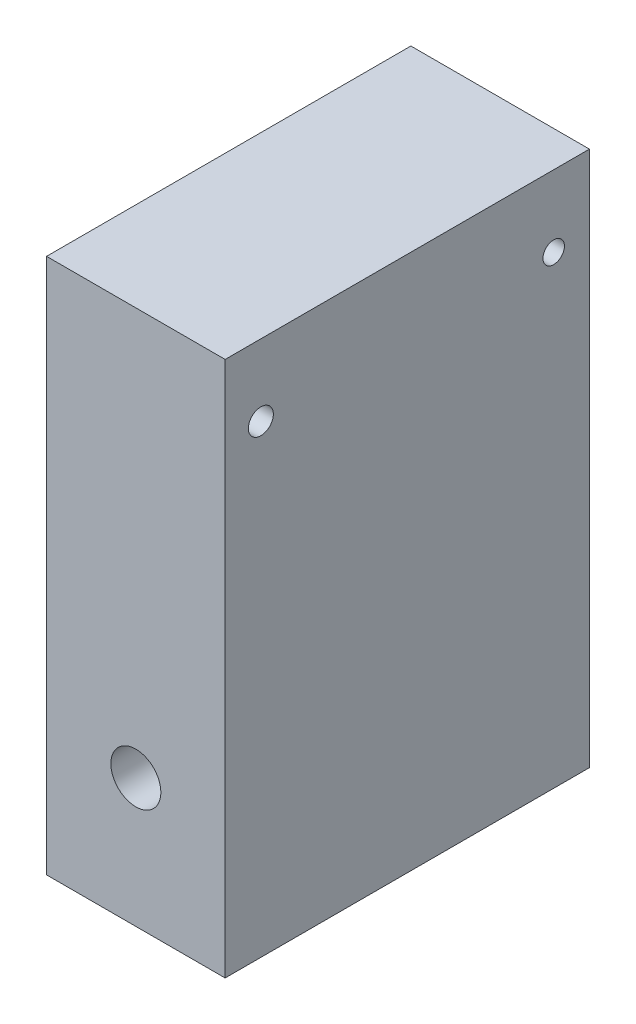
SolidWorks part; units mm, degrees
ref_plane "Plan de face" through (0, 0, 0) normal (0, 0, 1) x (1, 0, 0)
ref_plane "Plan de dessus" through (0, 0, 0) normal (0, 1, 0) x (1, 0, 0)
ref_plane "Plan de droite" through (0, 0, 0) normal (1, 0, 0) x (0, 0, -1)
sketch "Esquisse1" plane through (0, 0, 0) normal (0, 0, 1) x (1, 0, 0)
  line L1 (-6.525, 5.3902) -> (18.475, 5.3902)
  line L2 (-6.525, 5.3902) -> (-6.525, -69.6098)
  line L3 (-6.525, -69.6098) -> (18.475, -69.6098)
  line L4 (18.475, 5.3902) -> (18.475, -69.6098)
  dimension "D1" = 25
  dimension "D2" = 75
extrude "Boss.-Extru.1" add sketch "Esquisse1" along normal blind 51
sketch "Esquisse2" plane through (0, 0, 51) normal (0, 0, 1) x (1, 0, 0)
  line L1 (18.475, -69.6098) -> (18.475, 5.3902) construction
  line L2 (-6.525, -69.6098) -> (18.475, -69.6098) construction
  circle A0 centre (5.975, -51.6098) radius 3.5
  dimension "D1" = 7
  dimension "D2" = 18
  dimension "D3" = 12.5
extrude "Enlèv. mat.-Extru.1" cut sketch "Esquisse2" against normal blind 70
sketch "Esquisse3" plane through (0, -69.6098, 0) normal (0, -1, 0) x (1, 0, 0)
  line L1 (13.475, 5) -> (-1.525, 5)
  line L2 (13.475, 5) -> (13.475, 46)
  line L3 (13.475, 46) -> (-1.525, 46)
  line L4 (-1.525, 5) -> (-1.525, 46)
  line L6 (-6.525, 51) -> (-6.525, 0) construction
  line L7 (18.475, 51) -> (18.475, 0) construction
  line L8 (-6.525, 0) -> (18.475, 0) construction
  dimension "D1" = 41
  dimension "D2" = 5
  dimension "D3" = 5
  dimension "D4" = 5
extrude "Enlèv. mat.-Extru.2" cut sketch "Esquisse3" against normal blind 29
sketch "Esquisse4" plane through (18.475, 0, 0) normal (1, 0, 0) x (0, 0, -1)
  line L0 (-51, 5.3902) -> (0, 5.3902) construction
  line L1 (0, -69.6098) -> (0, 5.3902) construction
  line L2 (-51, -69.6098) -> (-51, 5.3902) construction
  circle A0 centre (-46, -4.6098) radius 1.75
  circle A1 centre (-5, -4.6098) radius 1.5
  dimension "D1" = 3.5
  dimension "D2" = 3
  dimension "D3" = 10
  dimension "D4" = 10
  dimension "D5" = 5
  dimension "D6" = 5
extrude "Enlèv. mat.-Extru.3" cut sketch "Esquisse4" against normal blind 25
